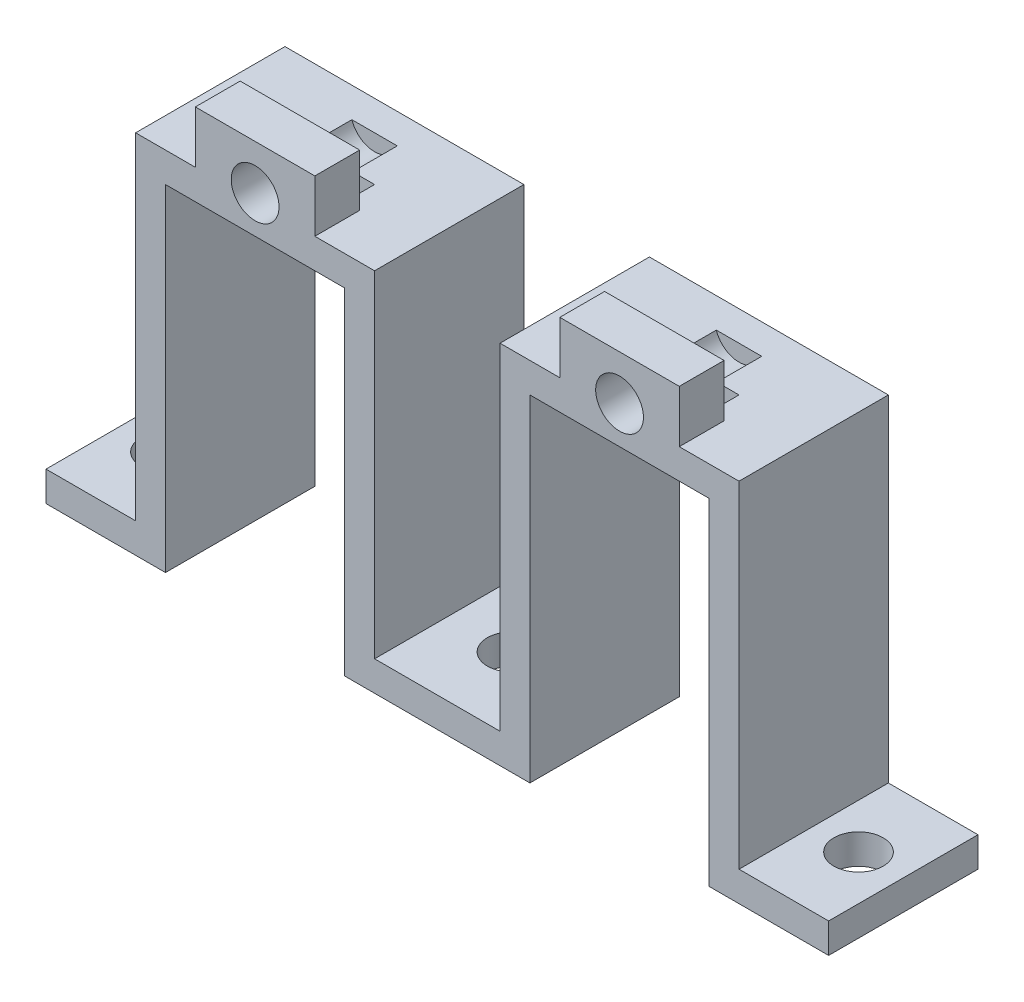
SolidWorks part; units mm, degrees
ref_plane "Alzado" through (0, 0, 0) normal (0, 0, 1) x (1, 0, 0)
ref_plane "Planta" through (0, 0, 0) normal (0, 1, 0) x (1, 0, 0)
ref_plane "Vista lateral" through (0, 0, 0) normal (1, 0, 0) x (0, 0, -1)
sketch "Croquis1" plane through (0, 0, 0) normal (0, 0, 1) x (1, 0, 0)
  line L0 (6.2, 0) -> (-6.2, 0)
  line L1 (-6.2, 0) -> (-6.2, 22.5)
  line L2 (-6.2, 22.5) -> (-18.2, 22.5)
  line L3 (-18.2, 22.5) -> (-18.2, 0)
  line L4 (-18.2, 0) -> (-26.2, 0)
  line L5 (0, 0) -> (0, 14.9625) construction
  line L6 (18.2, 0) -> (26.2, 0)
  line L7 (18.2, 22.5) -> (18.2, 0)
  line L8 (6.2, 22.5) -> (18.2, 22.5)
  line L9 (6.2, 0) -> (6.2, 22.5)
  dimension "D1" = 6.2
  dimension "D2" = 12
  dimension "D3" = 8
  dimension "D4" = 22.5
extrude "Extruir-Lámina1" add sketch "Croquis1" along normal blind 10 thin
sketch "Croquis2" plane through (0, 0, 10) normal (0, 0, 1) x (1, 0, 0)
  line L0 (-16.2, 24.5) -> (-16.2, 28)
  line L1 (-20.2, 24.5) -> (-4.2, 24.5) construction
  line L2 (-16.2, 28) -> (-8.2, 28)
  line L3 (-8.2, 28) -> (-8.2, 24.5)
  line L4 (-8.2, 24.5) -> (-16.2, 24.5)
  point P4 (-12.2, 24.5)
  point P7 (-12.2, 24.5)
  dimension "D1" = 3.5
  dimension "D3" = 8
extrude "Saliente-Extruir1" add sketch "Croquis2" against normal blind 3
mirror "Simetría1" about plane through (0, 0, 0) normal (1, 0, 0) of "Saliente-Extruir1"
sketch "Croquis3" plane through (0, 0, 0) normal (0, -1, 0) x (-1, 0, 0)
  line L0 (26.2, -5) -> (-26.2, -5) construction
  line L1 (26.2, -10) -> (26.2, 0) construction
  line L2 (-26.2, -10) -> (-26.2, 0) construction
  circle A0 centre (0, -5) radius 1.65
  circle A1 centre (23.2, -5) radius 1.65
  circle A2 centre (-23.2, -5) radius 1.65
  dimension "D1" = 3.3
  dimension "D2" = 3
  dimension "D3" = 3
extrude "Cortar-Extruir1" cut sketch "Croquis3" against normal through all
sketch "Croquis4" plane through (0, 0, 10) normal (0, 0, 1) x (1, 0, 0)
  line L0 (-12.2, 28) -> (-12.2, 22.5) construction
  line L1 (-8.2, 28) -> (-16.2, 28) construction
  line L2 (-18.2, 22.5) -> (-6.2, 22.5) construction
  circle A0 centre (-12.2, 25) radius 1.6
  dimension "D1" = 2.5
  dimension "D2" = 3.2
extrude "Cortar-Extruir2" cut sketch "Croquis4" against normal blind 8 contours A0
sketch "Croquis6" plane through (0, 24.5, 0) normal (0, 1, 0) x (1, 0, 0)
  line L0 (-9.2, -7) -> (-15.2, -7)
  line L3 (-15.2, -7) -> (-15.2, -5)
  line L4 (-15.2, -5) -> (-9.2, -5)
  line L5 (-9.2, -5) -> (-9.2, -7)
  line L6 (-12.2, -2) -> (-12.2, -7) construction
  line L7 (-13.7199, -2) -> (-10.6801, -2) construction
  dimension "D1" = 2
  dimension "D2" = 6
  dimension "D3" = 5
extrude "Cortar-Extruir3" cut sketch "Croquis6" against normal through all
mirror "Simetría2" about plane through (0, 0, 0) normal (1, 0, 0) of "Cortar-Extruir2", "Cortar-Extruir3"
equation "\"D3@Croquis3\"=\"D2@Croquis3\""
